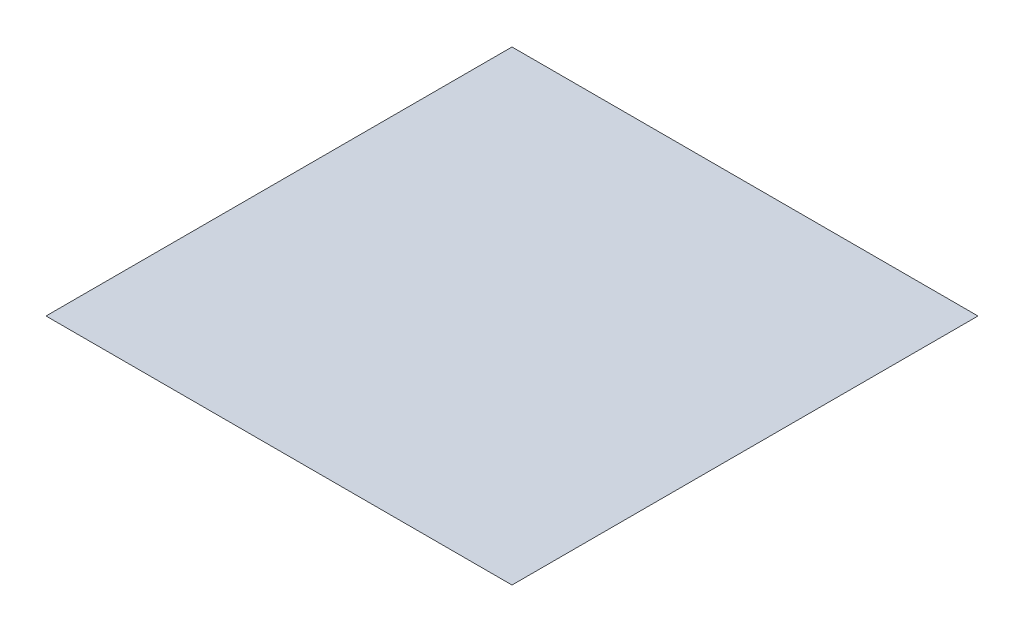
SolidWorks part; units mm, degrees
ref_plane "Front Plane" through (0, 0, 0) normal (0, 0, 1) x (1, 0, 0)
ref_plane "Top Plane" through (0, 0, 0) normal (0, 1, 0) x (1, 0, 0)
ref_plane "Right Plane" through (0, 0, 0) normal (1, 0, 0) x (0, 0, -1)
sketch "Sketch1" plane through (0, 0, 0) normal (0, 1, 0) x (1, 0, 0)
  line L1 (-500, -500) -> (500, -500)
  line L2 (-500, -500) -> (-500, 500)
  line L3 (-500, 500) -> (500, 500)
  line L4 (500, -500) -> (500, 500)
  line L5 (-500, -500) -> (500, 500) construction
  line L6 (-500, 500) -> (500, -500) construction
  point P0 (0, 0)
  dimension "D1" = 1000
  dimension "D2" = 1000
ref_plane "Plane1" through (0, -400, 0) normal (0, -1, 0) x (-1, 0, 0)
sketch "Sketch2" plane through (0, -400, 0) normal (0, -1, 0) x (-1, 0, 0)
  point P0 (0, 0)
loft "Loft1" add profiles "Sketch1", "Sketch2"
sketch "Sketch5" plane through (0, -400, 0) normal (0, -1, 0) x (-1, 0, 0)
  line L0 (500, 500) -> (0, 0) construction
  line L1 (-75, -75) -> (75, -75)
  line L2 (-75, -75) -> (-75, 75)
  line L3 (-75, 75) -> (75, 75)
  line L4 (75, -75) -> (75, 75)
  line L5 (-75, -75) -> (75, 75) construction
  line L6 (-75, 75) -> (75, -75) construction
  point P0 (0, 0)
  dimension "D1" = 150
  dimension "D2" = 150
extrude "Cut-Extrude1" cut sketch "Sketch5" against normal blind 100
